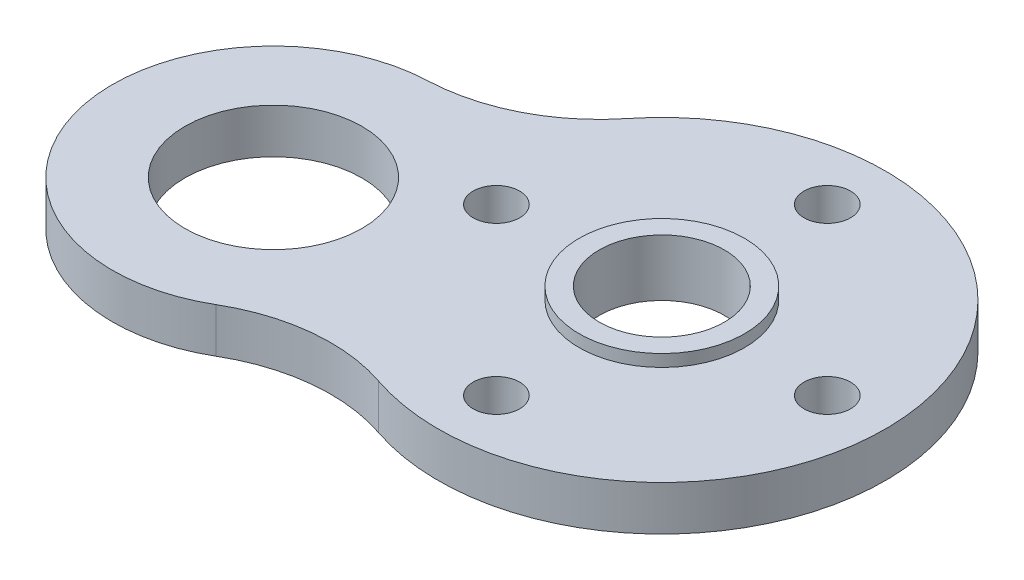
SolidWorks part; units mm, degrees
material "Nylon 101"
ref_plane "Alzado" through (0, 0, 0) normal (0, 0, 1) x (1, 0, 0)
ref_plane "Planta" through (0, 0, 0) normal (0, 1, 0) x (1, 0, 0)
ref_plane "Vista lateral" through (0, 0, 0) normal (1, 0, 0) x (0, 0, -1)
sketch "Sketch1" plane through (0, 0, 0) normal (0, 1, 0) x (1, 0, 0)
  circle A0 centre (0, 0) radius 18.5 construction
  circle A1 centre (0, 0) radius 25
  dimension "D1" = 37
  dimension "D2" = 50
sketch "Sketch2" plane through (0, 0, 0) normal (0, 1, 0) x (1, 0, 0)
  circle A0 centre (0, 0) radius 25
  circle A1 centre (0, 18.5) radius 2.6
  circle A2 centre (0, 0) radius 18.5 construction
  circle A3 centre (0, 0) radius 25 construction
  circle A4 centre (18.5, 0) radius 2.6
  circle A5 centre (0, -18.5) radius 2.6
  circle A6 centre (-18.5, 0) radius 2.6
  point P18 (0, 0)
  dimension "D1" = 5.2
  dimension "D2" = 4
extrude "Boss-Extrude1" add sketch "Sketch2" along normal blind 5
sketch "Sketch4" plane through (0, 5, 0) normal (0, 1, 0) x (1, 0, 0)
  circle A0 centre (0, 0) radius 9.25
  dimension "D1" = 18.5
extrude "Boss-Extrude2" add sketch "Sketch4" along normal blind 1.35
sketch "Sketch3" plane through (0, 6.35, 0) normal (0, 1, 0) x (1, 0, 0)
  circle A0 centre (0, 0) radius 7
  dimension "D1" = 14
extrude "Cut-Extrude1" cut sketch "Sketch3" against normal through all
sketch "Sketch5" plane through (0, 0, 0) normal (0, -1, 0) x (1, 0, 0)
  line L0 (0, 0) -> (-33.5854, 9.85) construction
  arc A0 (-17.4749, 17.8782) -> (-24.3629, -5.6079) centre (-33.5854, 9.85) ccw
  circle A1 centre (0, 0) radius 25 construction
  arc A2 (-17.4749, 17.8782) -> (-24.3629, -5.6079) centre (0, 0) ccw
  circle A3 centre (-33.5854, 9.85) radius 9.9
  dimension "D2" = 36
  dimension "D3" = 19.8
  dimension "D1" = 35
  dimension "D4" = 9.85
extrude "Boss-Extrude3" add sketch "Sketch5" against normal up to surface (5 mm away) up to face at (0, 5, 9.25)
fillet "Fillet1" radius 20 2 edges at (-17.4749, 2.5, 17.8782) (-24.3629, 2.5, -5.6079)
